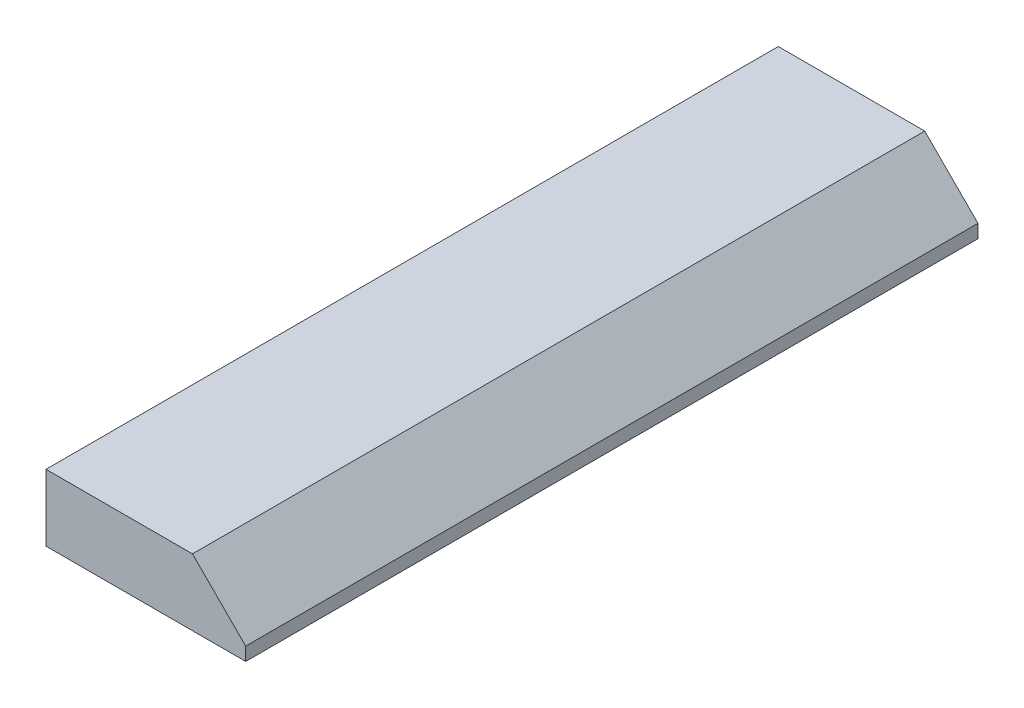
SolidWorks part; units mm, degrees
ref_plane "Front Plane" through (0, 0, 0) normal (0, 0, 1) x (1, 0, 0)
ref_plane "Top Plane" through (0, 0, 0) normal (0, 1, 0) x (1, 0, 0)
ref_plane "Right Plane" through (0, 0, 0) normal (1, 0, 0) x (0, 0, -1)
sketch "Sketch1" plane through (0, 0, 0) normal (0, 0, 1) x (1, 0, 0)
  line L0 (19.05, 1.27) -> (13.97, 6.35)
  line L1 (0, 0) -> (19.05, 0)
  line L2 (0, 0) -> (0, 6.35)
  line L3 (0, 6.35) -> (13.97, 6.35)
  line L4 (19.05, 1.27) -> (19.05, 0)
  dimension "D1" = 6.35
  dimension "D2" = 19.05
  dimension "D3" = 45
  dimension "D4" = 5.08
extrude "Boss-Extrude1" add sketch "Sketch1" along normal blind 69.85
